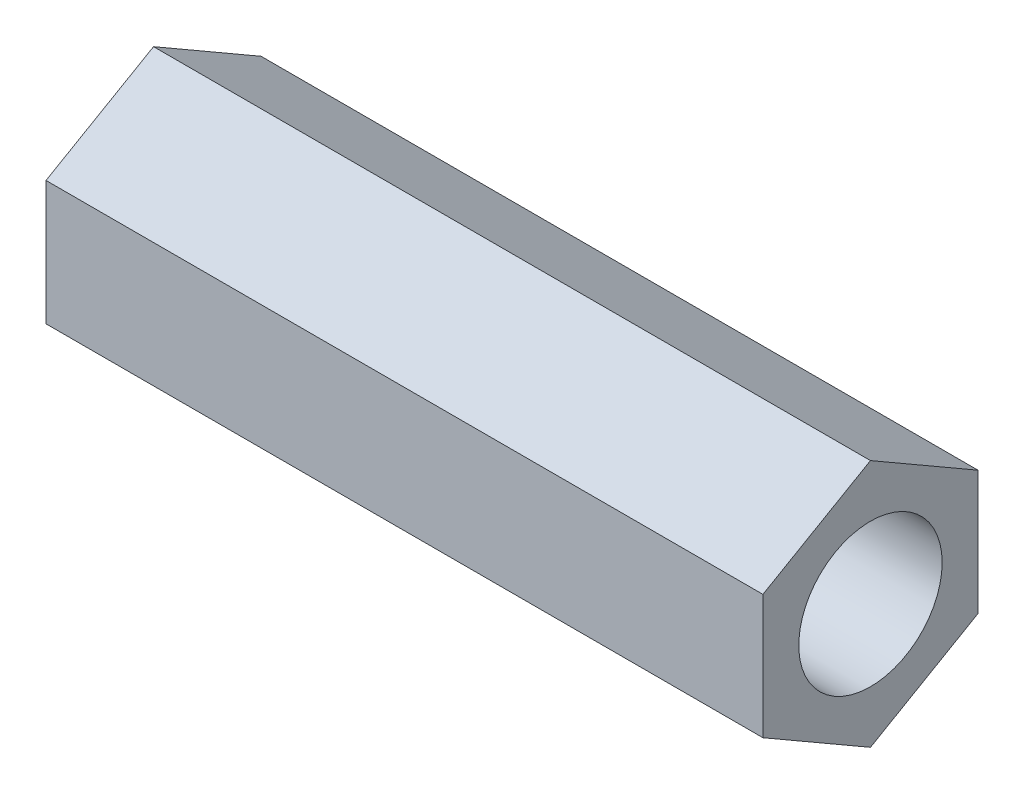
SolidWorks part; units mm, degrees
ref_plane "Front" through (0, 0, 0) normal (0, 0, 1) x (1, 0, 0)
ref_plane "Top" through (0, 0, 0) normal (0, 1, 0) x (1, 0, 0)
ref_plane "Right" through (0, 0, 0) normal (1, 0, 0) x (0, 0, -1)
sketch "草图1" plane through (0, 0, 0) normal (1, 0, 0) x (0, 0, -1)
  line L1 (0, 3.4641) -> (-3, 1.7321)
  line L2 (-3, 1.7321) -> (-3, -1.7321)
  line L3 (-3, -1.7321) -> (0, -3.4641)
  line L4 (0, -3.4641) -> (3, -1.7321)
  line L5 (3, -1.7321) -> (3, 1.7321)
  line L6 (3, 1.7321) -> (0, 3.4641)
  circle A0 centre (0, 0) radius 2
  circle A1 centre (0, 0) radius 3 construction
  dimension "D1" = 4
  dimension "D2" = 3
extrude "凸台-拉伸1" add sketch "草图1" along normal blind 20
